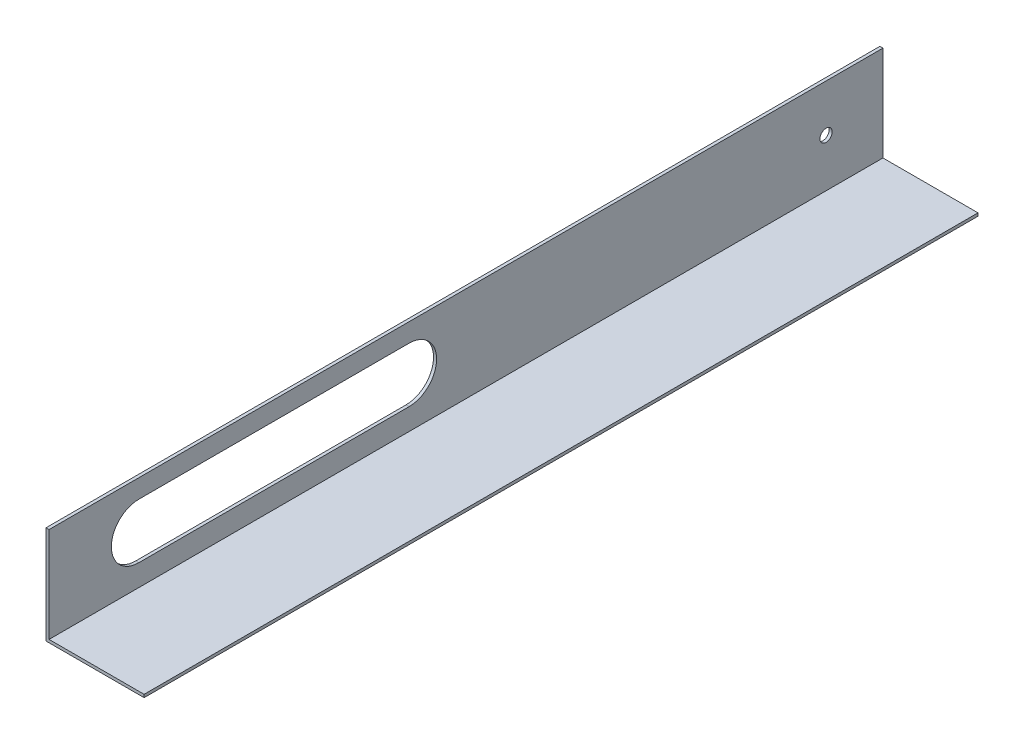
SolidWorks part; units mm, degrees
material "6061 Alloy"
ref_plane "Front Plane" through (0, 0, 0) normal (0, 0, 1) x (1, 0, 0)
ref_plane "Top Plane" through (0, 0, 0) normal (0, 1, 0) x (1, 0, 0)
ref_plane "Right Plane" through (0, 0, 0) normal (1, 0, 0) x (0, 0, -1)
sketch "Sketch3" plane through (0, 0, 0) normal (0, 0, 1) x (1, 0, 0)
  line L20 (49.2125, 1.5875) -> (49.2125, 50.8)
  line L21 (49.2125, 50.8) -> (50.8, 50.8)
  line L22 (50.8, 50.8) -> (50.8, 1.524)
  line L24 (50.8, 1.524) -> (100.0125, 1.524)
  line L25 (100.0125, 1.524) -> (100.0125, 0)
  line L26 (100.0125, 0) -> (49.2125, 0)
  line L27 (49.2125, 0) -> (49.2125, 1.5875)
  dimension "D1" = 50.8
  dimension "D2" = 1.524
  dimension "D3" = 1.5875
  dimension "D4" = 50.8
extrude "Boss-Extrude2" add sketch "Sketch3" along normal blind 431.8
sketch "Sketch8" plane through (50.8, 0, 0) normal (1, 0, 0) x (0, 0, -1)
  line L0 (-431.8, 50.8) -> (-431.8, 0) construction
  line L1 (-245.364, 26.924) -> (-385.318, 26.924) construction
  line L2 (-245.364, 12.7) -> (-385.318, 12.7)
  line L3 (-245.364, 41.148) -> (-385.318, 41.148)
  line L4 (-431.8, 50.8) -> (0, 50.8) construction
  line L5 (0, 1.524) -> (0, 50.8) construction
  line L6 (0, 1.524) -> (0, 50.8) construction
  line L7 (-431.8, 50.8) -> (0, 50.8) construction
  arc A1 (-245.364, 12.7) -> (-245.364, 41.148) centre (-245.364, 26.924) ccw
  arc A2 (-385.318, 41.148) -> (-385.318, 12.7) centre (-385.318, 26.924) ccw
  circle A3 centre (-29.464, 26.416) radius 3.175
  point P1 (-399.542, 26.924)
  point P6 (-315.341, 26.924)
  point P11 (-231.14, 26.924)
  dimension "D1" = 231.14
  dimension "D2" = 32.258
  dimension "D4" = 6.35
  dimension "D3" = 28.448
  dimension "D5" = 29.464
  dimension "D6" = 24.384
  dimension "D7" = 9.652
extrude "Cut-Extrude6" cut sketch "Sketch8" against normal blind 2.54
ref_plane "Plane1" through (241.3, 0, 0) normal (1, 0, 0) x (0, 0, -1)
